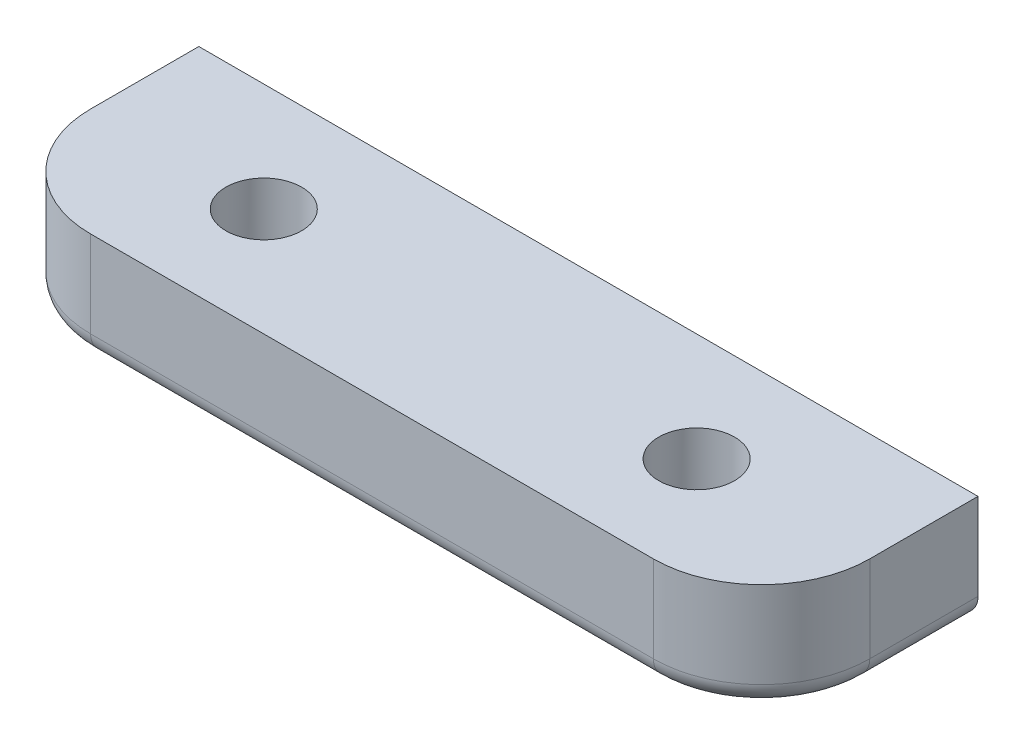
SolidWorks part; units mm, degrees
ref_plane "Front" through (0, 0, 0) normal (0, 0, 1) x (1, 0, 0)
ref_plane "Top" through (0, 0, 0) normal (0, 1, 0) x (1, 0, 0)
ref_plane "Right" through (0, 0, 0) normal (1, 0, 0) x (0, 0, -1)
sketch "Эскиз1" plane through (0, 0, 0) normal (0, 0, 1) x (1, 0, 0)
  line L1 (-18, 2.5) -> (18, 2.5)
  line L2 (-18, 2.5) -> (-18, -2.5)
  line L3 (-18, -2.5) -> (18, -2.5)
  line L4 (18, 2.5) -> (18, -2.5)
  point P4 (0, 2.5)
  point P5 (18, 0)
  dimension "D1" = 5
  dimension "D2" = 36
extrude "Основа" add sketch "Эскиз1" along normal mid plane 10
sketch "Эскиз2" [suppressed] plane through (0, 0, -5) normal (0, 0, -1) x (-1, 0, 0)
  line L0 (14.75, -0.5) -> (14.75, 0) construction
  line L1 (14.75, 0) -> (-14.75, 0) construction
  circle A0 centre (-14.75, 0) radius 1
  circle A1 centre (14.75, -0.5) radius 1
  point P4 (0, 0)
  dimension "D1" = 29.5
  dimension "D3" = 2
  dimension "D2" = 0.5
extrude "Под крепление датчика_i2c_слева" [suppressed] cut sketch "Эскиз2" against normal blind 9
sketch "Эскиз4" plane through (0, 0, -5) normal (0, 0, -1) x (-1, 0, 0)
  line L0 (14.75, 0) -> (-14.75, 0) construction
  line L1 (-14.75, 0) -> (-14.75, -0.5) construction
  circle A0 centre (-14.75, -0.5) radius 1
  circle A1 centre (14.75, 0) radius 1
  point P7 (0, 0)
  dimension "D1" = 2
  dimension "D2" = 0.5
  dimension "D3" = 29.5
extrude "Под крепление датчика_i2c_справа" cut sketch "Эскиз4" against normal blind 9
sketch "Эскиз5" plane through (0, 2.5, 0) normal (0, 1, 0) x (1, 0, 0)
  line L0 (-10, 0) -> (10, 0) construction
  circle A0 centre (-10, 0) radius 1.75
  circle A1 centre (10, 0) radius 1.75
  circle A2 centre (-10, 0) radius 3.5 construction
  point P5 (0, 0)
  dimension "D1" = 20
  dimension "D2" = 3.5
  dimension "D3" = 7
extrude "Под крепление шурупов к плате" cut sketch "Эскиз5" against normal through all
sketch "Эскиз6" plane through (0, -2.5, 0) normal (0, 1, 0) x (1, 0, 0)
  circle A0 centre (-10, 0) radius 3.2
  circle A1 centre (10, 0) radius 3.2
  circle A2 centre (10, 0) radius 1.75 construction
  circle A3 centre (-10, 0) radius 1.75 construction
  dimension "D1" = 6.4
extrude "Под головы винтов" cut sketch "Эскиз6" along normal offset from surface (2 mm away) 3 up to face at (-10, 2.5, 1.75)
fillet "Скругление1" radius 5 2 edges at (-18, 0, 5) (18, 0, 5)
fillet "Скругление2" radius 1 5 edges at (-18, -2.5, -2.5) (-16.5355, -2.5, 3.5355) (18, -2.5, -2.5) (16.5355, -2.5, 3.5355) (0, -2.5, 5)
